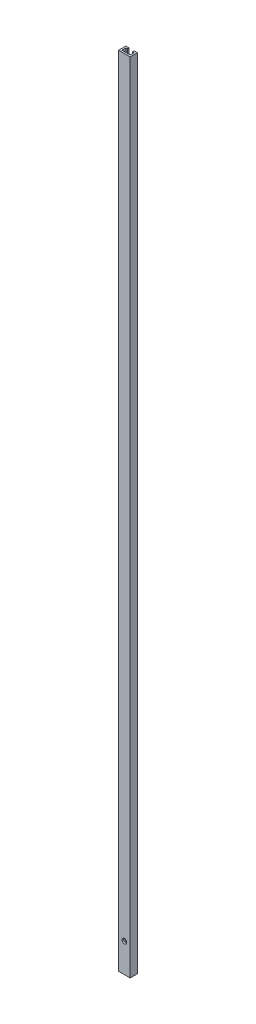
SolidWorks part; units mm, degrees
ref_plane "前视基准面" through (0, 0, 0) normal (0, 0, 1) x (1, 0, 0)
ref_plane "上视基准面" through (0, 0, 0) normal (0, 1, 0) x (1, 0, 0)
ref_plane "右视基准面" through (0, 0, 0) normal (1, 0, 0) x (0, 0, -1)
sketch "草图1" plane through (0, 0, 0) normal (0, 1, 0) x (1, 0, 0)
  line L0 (0, -5) -> (8, -5)
  line L1 (8, -5) -> (8, 0)
  line L2 (8, 0) -> (5.75, 0)
  line L3 (5.75, 0) -> (5.75, -1.15)
  line L4 (5.75, -1.15) -> (6.85, -1.15)
  line L5 (6.85, -1.15) -> (6.85, -3.85)
  line L6 (6.85, -3.85) -> (1.15, -3.85)
  line L7 (1.15, -3.85) -> (1.15, -1.15)
  line L8 (1.15, -1.15) -> (2.25, -1.15)
  line L9 (2.25, -1.15) -> (2.25, 0)
  line L10 (2.25, 0) -> (0, 0)
  line L11 (0, 0) -> (0, -5)
  line L12 (4, -3.85) -> (4, -5) construction
  line L13 (2.25, 0) -> (5.75, 0) construction
  line L14 (4, 0) -> (4, -3.85) construction
  dimension "D1" = 5
  dimension "D2" = 8
  dimension "D3" = 1.15
  dimension "D4" = 1.15
  dimension "D5" = 1.15
  dimension "D6" = 3.5
  dimension "D7" = 5.7
extrude "凸台-拉伸1" add sketch "草图1" along normal blind 550
sketch "草图2" plane through (0, 0, 5) normal (0, 0, 1) x (1, 0, 0)
  line L0 (0, 0) -> (8, 0) construction
  line L1 (4, 20) -> (4, 0) construction
  line L2 (0, 550) -> (8, 550) construction
  circle A0 centre (4, 20) radius 1.6
  dimension "D2" = 3.2
  dimension "D1" = 530
extrude "切除-拉伸1" cut sketch "草图2" against normal up to surface (1.15 mm away) up to face at (4, 275, 3.85)
